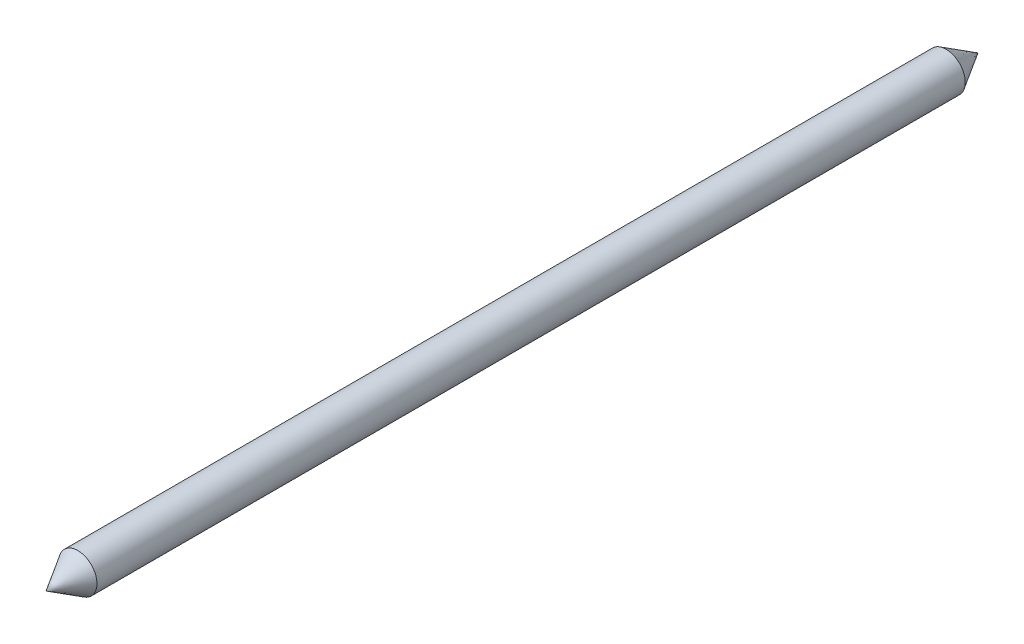
SolidWorks part; units mm, degrees
ref_plane "Front Plane" through (0, 0, 0) normal (0, 0, 1) x (1, 0, 0)
ref_plane "Top Plane" through (0, 0, 0) normal (0, 1, 0) x (1, 0, 0)
ref_plane "Right Plane" through (0, 0, 0) normal (1, 0, 0) x (0, 0, -1)
sketch "Sketch2" plane through (0, 0, 0) normal (0, 1, 0) x (1, 0, 0)
  line L0 (7.62, 173.0375) -> (7.62, -173.0375)
  line L1 (7.62, -173.0375) -> (0, -185.7375)
  line L2 (0, -185.7375) -> (0, 185.7375)
  line L3 (0, 185.7375) -> (7.62, 173.0375)
  point P2 (0, 0)
  dimension "D1" = 12.7
  dimension "D2" = 12.7
  dimension "D3" = 371.475
  dimension "D4" = 7.62
revolve "Revolve1" add sketch "Sketch2" angle 360 about L2
